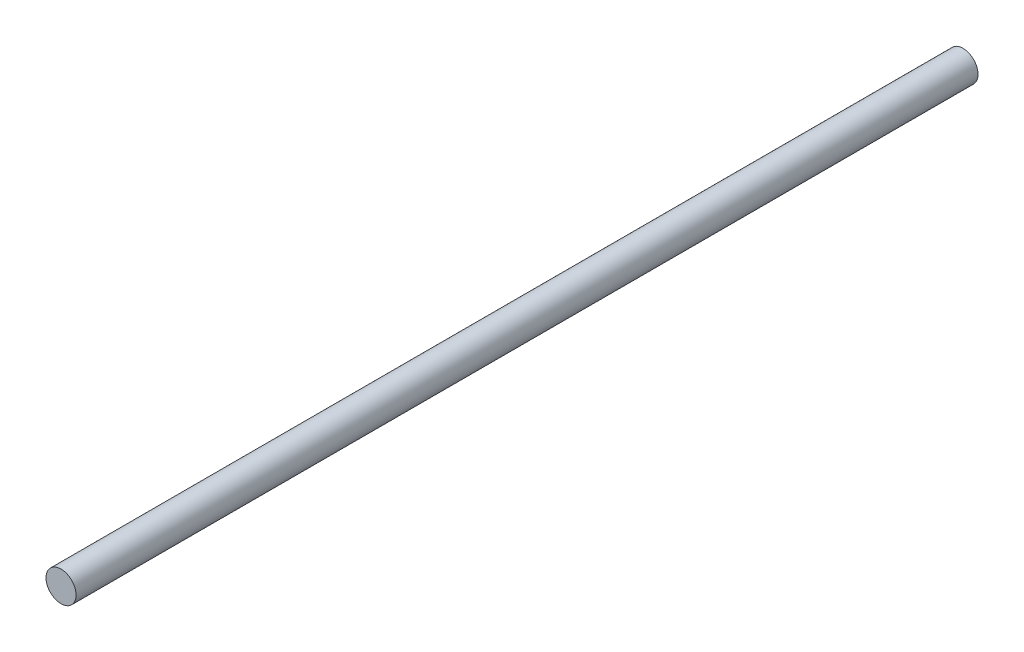
SolidWorks part; units mm, degrees
material "GCr15"
ref_plane "前视基准面" through (0, 0, 0) normal (0, 0, 1) x (1, 0, 0)
ref_plane "上视基准面" through (0, 0, 0) normal (0, 1, 0) x (1, 0, 0)
ref_plane "右视基准面" through (0, 0, 0) normal (1, 0, 0) x (0, 0, -1)
sketch "草图1" plane through (0, 0, 0) normal (0, 0, 1) x (1, 0, 0)
  circle A1 centre (0, 0) radius 3
  dimension "D1" = 6
extrude "拉伸1" add sketch "草图1" along normal blind 180
